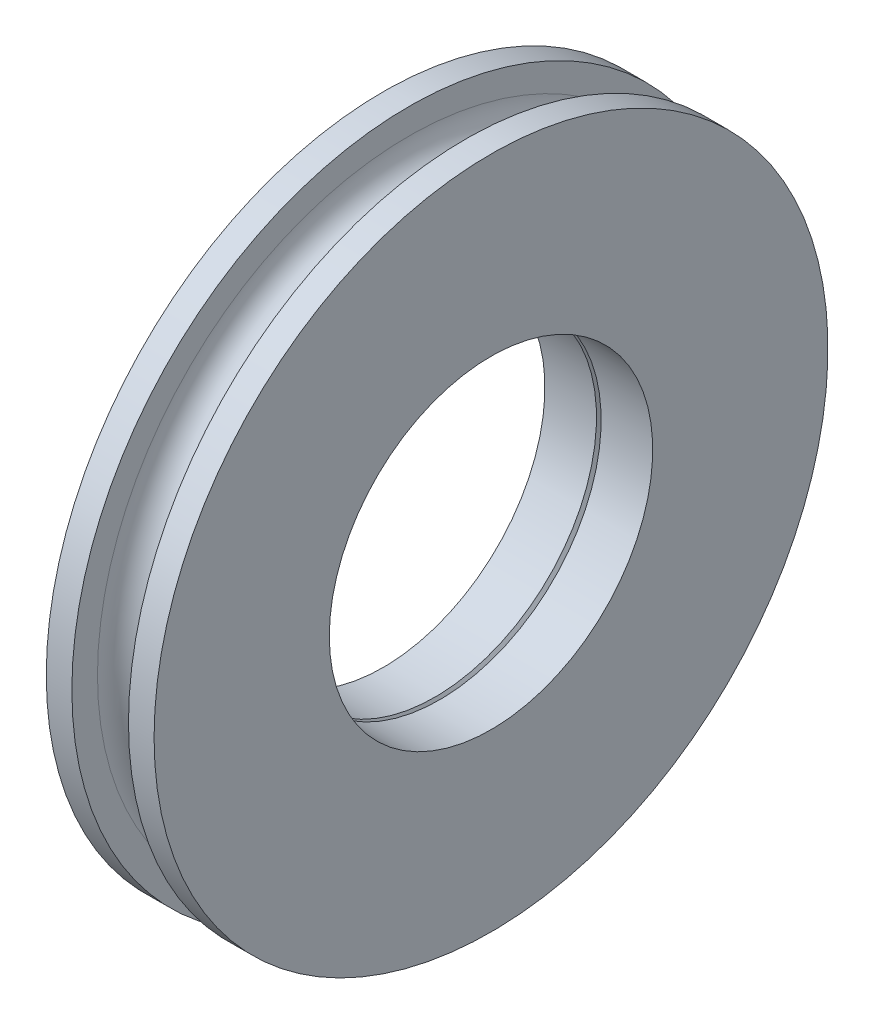
SolidWorks part; units mm, degrees
ref_plane "Front Plane" through (0, 0, 0) normal (0, 0, 1) x (1, 0, 0)
ref_plane "Top Plane" through (0, 0, 0) normal (0, 1, 0) x (1, 0, 0)
ref_plane "Right Plane" through (0, 0, 0) normal (1, 0, 0) x (0, 0, -1)
ref_plane "Plane1" through (0, 0, 0) normal (0, 0, -1) x (-1, 0, 0)
sketch "Sketch1" plane through (0, 0, 0) normal (0, 0, -1) x (-1, 0, 0)
  line L0 (4, 25) -> (2.1, 25)
  line L1 (2.1, 25) -> (2.1, 23.1)
  line L2 (-2.1, 23.1) -> (-2.1, 25)
  line L3 (-2.1, 25) -> (-4, 25)
  line L4 (-4, 25) -> (-4, 12)
  line L5 (-4, 12) -> (-0.1732, 12)
  line L6 (-0.1732, 12) -> (0, 12.3)
  line L7 (0, 12.3) -> (0.1732, 12)
  line L8 (0.1732, 12) -> (4, 12)
  line L9 (4, 12) -> (4, 25)
  line L10 (-3, 0) -> (3, 0) construction
  line L11 (0, 23.1) -> (0, 0) construction
  arc A0 (2.1, 23.1) -> (-2.1, 23.1) centre (0, 23.1) cw
  dimension "D4" = 8
  dimension "D1" = 12
  dimension "D2" = 25
  dimension "D3" = 23.1
revolve "Revolve1" add sketch "Sketch1" angle 360 about L10
